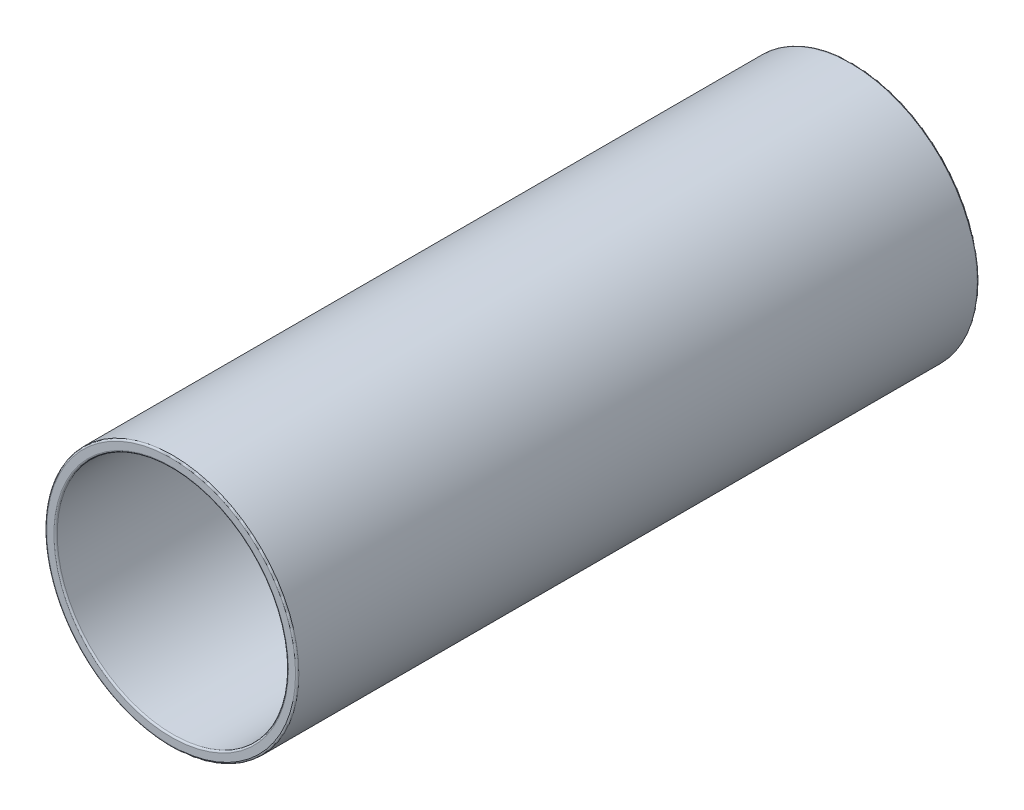
SolidWorks part; units mm, degrees
ref_plane "Front Plane" through (0, 0, 0) normal (0, 0, 1) x (1, 0, 0)
ref_plane "Top Plane" through (0, 0, 0) normal (0, 1, 0) x (1, 0, 0)
ref_plane "Right Plane" through (0, 0, 0) normal (1, 0, 0) x (0, 0, -1)
sketch "Sketch1" plane through (0, 0, 0) normal (0, 0, 1) x (1, 0, 0)
  circle A0 centre (0, 0) radius 69.85
  circle A1 centre (0, 0) radius 76.2
  dimension "D1" = 139.7
  dimension "D2" = 152.4
extrude "Boss-Extrude1" add sketch "Sketch1" along normal mid plane 412
fillet "Fillet1" radius 1 4 edges at (76.2, 0, -206) (76.2, 0, 206) (69.85, 0, -206) (69.85, 0, 206)
